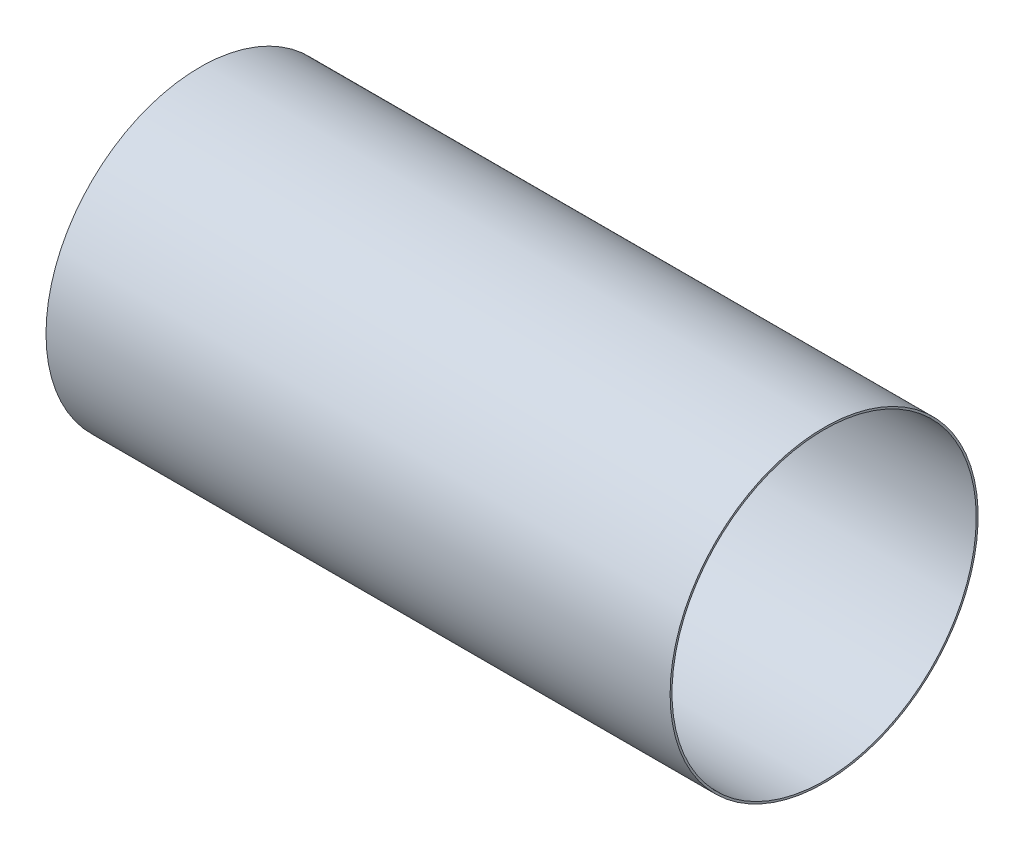
SolidWorks part; units mm, degrees
ref_plane "Front Plane" through (0, 0, 0) normal (0, 0, 1) x (1, 0, 0)
ref_plane "Top Plane" through (0, 0, 0) normal (0, 1, 0) x (1, 0, 0)
ref_plane "Right Plane" through (0, 0, 0) normal (1, 0, 0) x (0, 0, -1)
sketch "Sketch2" plane through (0, 0, 0) normal (1, 0, 0) x (0, 0, -1)
  circle A0 centre (0, 0) radius 75.2221
  dimension "D1" = 150.4442
extrude "Boss-Extrude1" add sketch "Sketch2" along normal blind 304.8
sketch "Sketch3" plane through (304.8, 0, 0) normal (1, 0, 0) x (0, 0, -1)
  circle A0 centre (0, 0) radius 74.2823
  dimension "D1" = 148.5646
extrude "Cut-Extrude1" cut sketch "Sketch3" against normal through all
